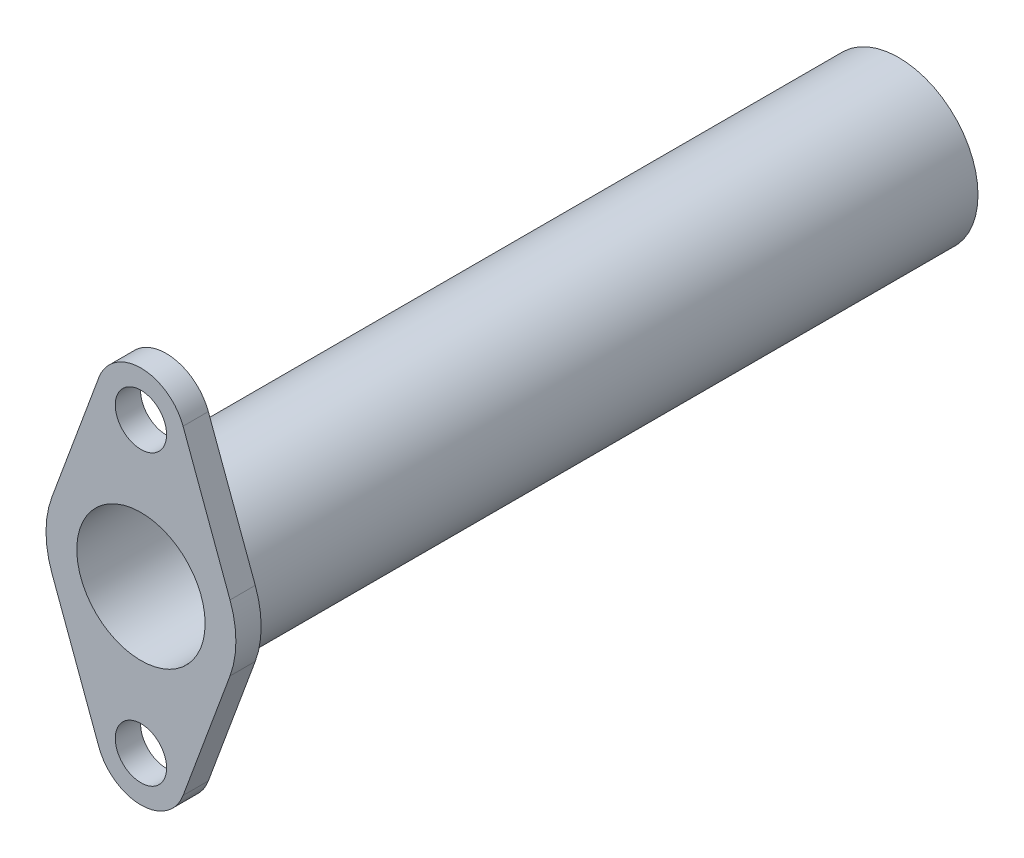
SolidWorks part; units mm, degrees
material "6061-T6 (SS)"
ref_plane "Front Plane" through (0, 0, 0) normal (0, 0, 1) x (1, 0, 0)
ref_plane "Top Plane" through (0, 0, 0) normal (0, 1, 0) x (1, 0, 0)
ref_plane "Right Plane" through (0, 0, 0) normal (1, 0, 0) x (0, 0, -1)
sketch "Sketch1" plane through (0, 0, 0) normal (0, 0, 1) x (1, 0, 0)
  line L0 (-17.6006, 0) -> (17.3059, 0) construction
  line L1 (-8.3387, 31.6569) -> (-17.6304, 6.5159)
  line L2 (8.3387, 31.6569) -> (17.6304, 6.5159)
  line L3 (-8.3387, -31.6569) -> (-17.6304, -6.5159)
  line L4 (8.3387, -31.6569) -> (17.6304, -6.5159)
  circle A0 centre (0, 0) radius 12.7
  circle A1 centre (0, 28.575) radius 8.89
  circle A2 centre (0, -28.575) radius 8.89
  circle A3 centre (0, 0) radius 18.796
  circle A4 centre (0, 28.575) radius 5.08
  circle A5 centre (0, -28.575) radius 5.08
  dimension "D1" = 25.4
  dimension "D3" = 17.78
  dimension "D4" = 37.592
  dimension "D5" = 10.16
  dimension "D2" = 57.15
extrude "Boss-Extrude1" add sketch "Sketch1" against normal blind 5
sketch "Sketch2" plane through (0, 0, 0) normal (0, 0, 1) x (1, 0, 0)
  circle A0 centre (0, 0) radius 15.7
  circle A1 centre (0, 0) radius 12.7
  dimension "D1" = 25.4
  dimension "D2" = 3
extrude "Boss-Extrude2" add sketch "Sketch2" against normal blind 150
sketch "Sketch3" plane through (0, 0, -150) normal (0, 0, -1) x (-1, 0, 0)
  circle A0 centre (0, 0) radius 15.7
  dimension "D1" = 31.4
ref_plane "Plane1" through (0, 25, 0) normal (0, 1, 0) x (1, 0, 0)
ref_plane "Plane2" through (0, 0, -150) normal (0, 0, 1) x (1, 0, 0)
